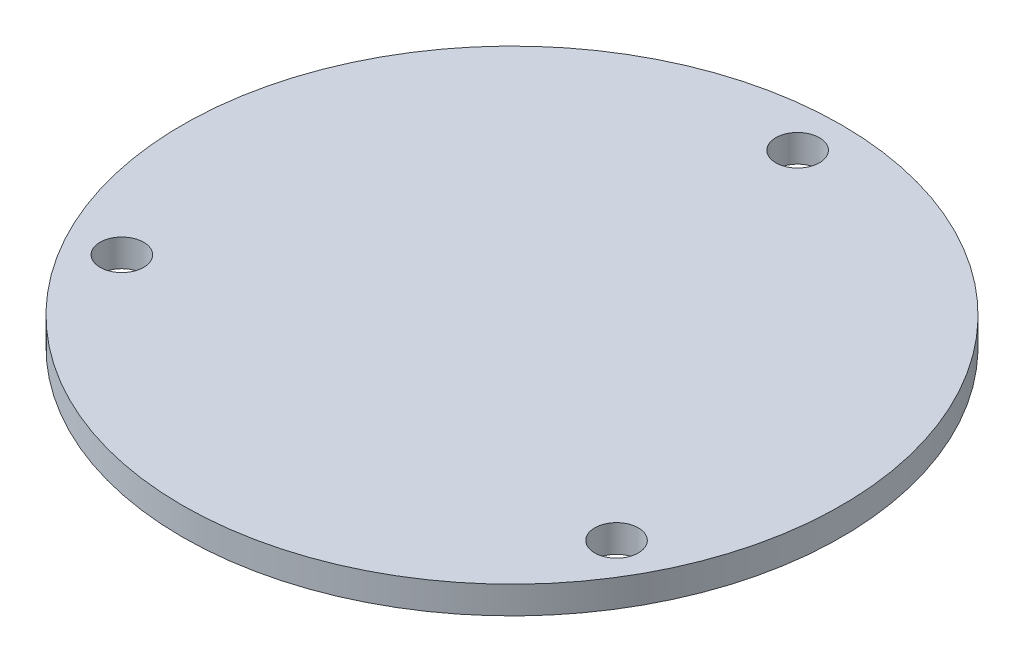
SolidWorks part; units mm, degrees
material "A-Glass Fiber"
ref_plane "Front Plane" through (0, 0, 0) normal (0, 0, 1) x (1, 0, 0)
ref_plane "Top Plane" through (0, 0, 0) normal (0, 1, 0) x (1, 0, 0)
ref_plane "Right Plane" through (0, 0, 0) normal (1, 0, 0) x (0, 0, -1)
sketch "Sketch1" plane through (0, 0, 0) normal (0, 1, 0) x (1, 0, 0)
  line L0 (19.05, 35.56) -> (19.05, 19.05) construction
  line L1 (19.05, 19.05) -> (4.7519, 10.795) construction
  line L2 (19.05, 19.05) -> (33.3481, 10.795) construction
  circle A0 centre (19.05, 19.05) radius 19.05
  circle A1 centre (19.05, 35.56) radius 1.2598
  circle A2 centre (4.7519, 10.795) radius 1.2598
  circle A3 centre (33.3481, 10.795) radius 1.2598
  dimension "D1" = 38.1
  dimension "D4" = 2.5196
  dimension "D2" = 19.05
  dimension "D3" = 19.05
  dimension "D5" = 35.56
  dimension "D6" = 120
  dimension "D7" = 120
  dimension "D8" = 10.795
  dimension "D9" = 4.7519
  dimension "D10" = 33.3481
extrude "Boss-Extrude1" add sketch "Sketch1" along normal blind 1.5875
sketch "Sketch2" plane through (0, 1.5875, 0) normal (0, 1, 0) x (1, 0, 0)
  circle A0 centre (19.05, 19.05) radius 16.51
  circle A1 centre (19.05, 19.05) radius 19.05 construction
  point P4 (19.05, 35.56)
  dimension "D1" = 33.02
